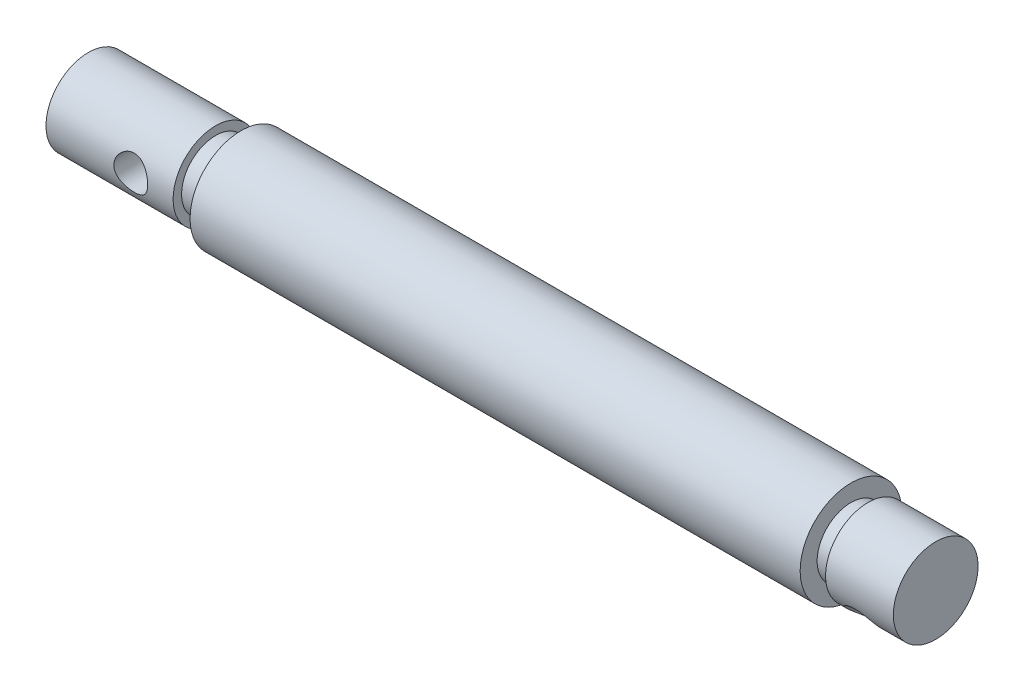
SolidWorks part; units mm, degrees
ref_plane "前视基准面" through (0, 0, 0) normal (0, 0, 1) x (1, 0, 0)
ref_plane "上视基准面" through (0, 0, 0) normal (0, 1, 0) x (1, 0, 0)
ref_plane "右视基准面" through (0, 0, 0) normal (1, 0, 0) x (0, 0, -1)
sketch "草图1" plane through (0, 0, 0) normal (0, 0, 1) x (1, 0, 0)
  line L0 (0, 0) -> (100, 0) construction
  line L1 (0, 0) -> (0, 5)
  line L2 (0, -55) -> (0, 55) construction
  line L3 (0, 5) -> (15, 5)
  line L4 (15, 5) -> (15, 4)
  line L5 (15, 4) -> (18, 4)
  line L6 (18, 4) -> (18, 6)
  line L7 (18, 6) -> (90, 6)
  line L8 (90, 6) -> (90, 4)
  line L9 (90, 4) -> (92, 4)
  line L10 (92, 4) -> (92, 5)
  line L11 (92, 5) -> (100, 5)
  line L12 (100, 5) -> (100, 0)
  line L13 (0, 0) -> (100, 0)
  dimension "D1" = 100
  dimension "D2" = 10
  dimension "D3" = 12
  dimension "D4" = 10
  dimension "D5" = 3
  dimension "D6" = 1
  dimension "D7" = 2
  dimension "D8" = 1
  dimension "D9" = 18
  dimension "D10" = 10
revolve "旋转1" add sketch "草图1" angle 360 about L0
sketch "草图2" plane through (0, 0, 0) normal (0, 0, 1) x (1, 0, 0)
  line L0 (6.6, 0) -> (-6.6, 0) construction
  line L1 (18, 6) -> (18, -6) construction
  circle A0 centre (10, 0) radius 2
  dimension "D1" = 4
  dimension "D2" = 8
extrude "切除-拉伸1" cut sketch "草图2" against normal through all both and the other way through all
ref_plane "基准面1" through (95, 0, 0) normal (1, 0, 0) x (0, 0, -1)
sketch "草图4" plane through (95, 0, 0) normal (1, 0, 0) x (0, 0, -1)
  line L0 (0, 0) -> (-3.5355, -3.5355) construction
  line L1 (6.6, 0) -> (-6.6, 0) construction
  line L2 (-2.1213, -2.1213) -> (-2.1213, -4.9497)
  line L3 (-2.1213, -4.9497) -> (-3.5355, -3.5355)
  line L4 (-3.5355, -3.5355) -> (-2.1213, -2.1213)
  circle A0 centre (0, 0) radius 5 construction
  point P9 (-4.9497, -4.9497)
  point P10 (-4.9034, -4.9497)
  point P11 (-2.0515, -2.533)
  dimension "D1" = 135
  dimension "D2" = 4
  dimension "D3" = 45
revolve "切除-旋转1" cut sketch "草图4" angle 360 about L0
